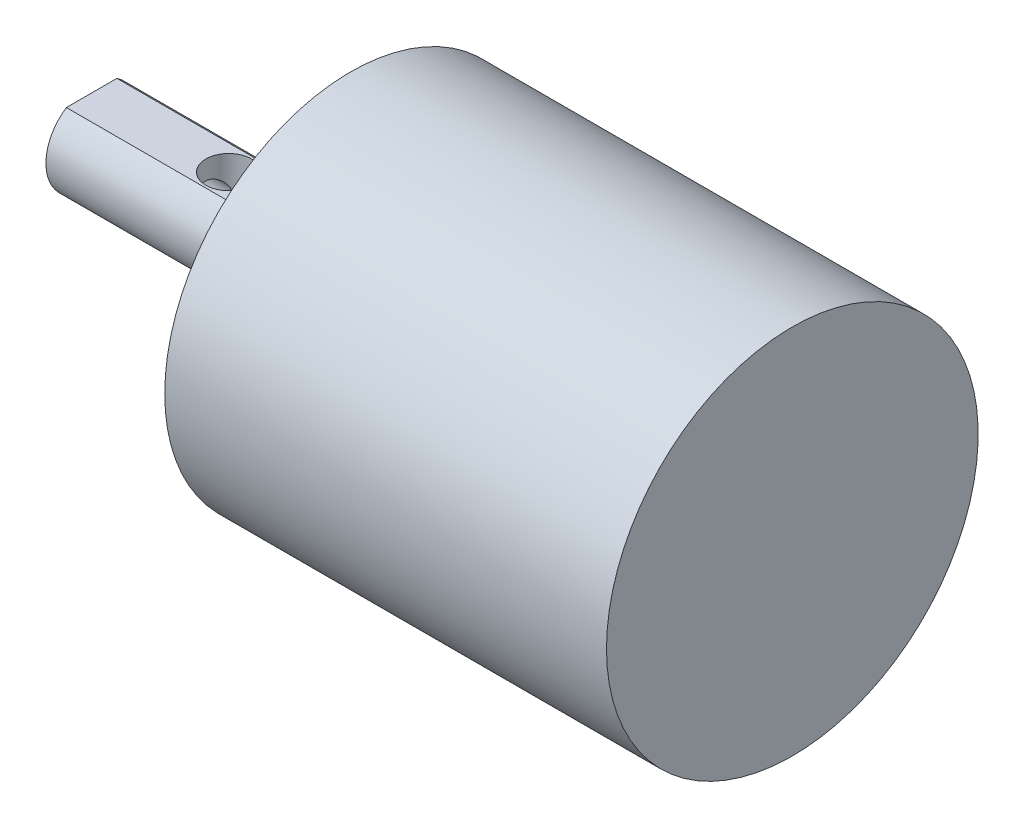
SolidWorks part; units mm, degrees
ref_plane "前视基准面" through (0, 0, 0) normal (0, 0, 1) x (1, 0, 0)
ref_plane "上视基准面" through (0, 0, 0) normal (0, 1, 0) x (1, 0, 0)
ref_plane "右视基准面" through (0, 0, 0) normal (1, 0, 0) x (0, 0, -1)
sketch "草图1" plane through (0, 0, 0) normal (0, 1, 0) x (1, 0, 0)
  line L0 (0, 0) -> (-29, 0)
  line L1 (-29, 0) -> (-29, 5.7)
  line L2 (-29, 5.7) -> (-31.6, 5.7)
  line L3 (-31.6, 5.7) -> (-31.6, 9.2)
  line L4 (-31.6, 9.2) -> (-46, 9.2)
  line L5 (-46, 9.2) -> (-46, 12.2)
  line L6 (-46, 12.2) -> (0, 12.2)
  line L7 (0, 12.2) -> (0, 0)
  dimension "D1" = 29
  dimension "D2" = 5.7
  dimension "D3" = 2.6
  dimension "D4" = 3.5
  dimension "D5" = 14.4
  dimension "D6" = 3
revolve "旋转1" add sketch "草图1" angle 360 about L6
sketch "草图2" plane through (-46, 0, 0) normal (-1, 0, 0) x (0, 0, 1)
  point P0 (-12.2, 0)
sketch "草图9" plane through (-46, 0, 0) normal (-1, 0, 0) x (0, 0, 1)
  line L0 (-12.2, 2.5) -> (-10.5417, 2.5)
  line L1 (-12.2, 2.5) -> (-13.8583, 2.5)
  line L2 (-13.8583, 2.5) -> (-12.2, 2.5)
  circle A0 centre (-12.2, 0) radius 3 construction
  arc A1 (-10.5417, 2.5) -> (-13.8583, 2.5) centre (-12.2, 0) ccw
extrude "切除-拉伸3" cut sketch "草图9" against normal blind 11.5 contours L1 A1 L0
hole_wizard "M3 螺纹孔1" positions "草图10" profile "草图11" tap size "M3" standard "GB"
sketch "草图10" plane through (-46, 0, 0) normal (-1, 0, 0) x (0, 0, 1)
  point P0 (-12.2, 0)
sketch "草图11" plane through (-46, 0, -12.2) normal (0, 1, 0) x (0, 0, 1)
  line L0 (0, 0) -> (0, 8.7511)
  line L1 (0, 8.7511) -> (1.25, 8)
  line L2 (1.25, 8) -> (1.25, 0)
  line L5 (1.25, 0) -> (0, 0)
  line L10 (0, 8.7511) -> (-1.25, 8) construction
  line L11 (0, -6.35) -> (0, 107.95) construction
  dimension "螺纹孔钻头直径" = 2.5
  dimension "螺纹孔钻头深度" = 8
  dimension "导头角度" = 118
cosmetic thread "孔螺蚊线2" parameters "D1"=5.5, "D2"=3
sketch "草图12" plane through (0, 2.5, 0) normal (0, 1, 0) x (1, 0, 0)
  line L0 (-46, 10.5417) -> (-46, 13.8583) construction
  circle A0 centre (-37, 12.2) radius 1.5
  point P0 (-37, 12.2)
  dimension "D1" = 3
  dimension "D2" = 9
extrude "切除-拉伸4" cut sketch "草图12" against normal blind 11.5 contours A0
sketch "草图13" plane through (-29, 0, 0) normal (-1, 0, 0) x (0, 0, 1)
  circle A1 centre (-12.2, 9.5) radius 1.5
  circle A2 centre (-3.9728, -4.75) radius 1.5
  circle A3 centre (-20.4272, -4.75) radius 1.5
  point P11 (-12.2, 0)
  dimension "D2" = 3
  dimension "D3" = 3
hole_wizard "M3 螺纹孔2" positions "草图14" profile "草图15" tap size "M3" standard "GB"
sketch "草图14" plane through (-29, 0, 0) normal (-1, 0, 0) x (0, 0, 1)
  point P2 (-12.2, 9.5)
  point P5 (-20.4272, -4.75)
  point P8 (-3.9728, -4.75)
sketch "草图15" plane through (-29, 9.5, -12.2) normal (0, 1, 0) x (0, 0, 1)
  line L0 (0, 0) -> (0, 4.7511)
  line L1 (0, 4.7511) -> (1.25, 4)
  line L2 (1.25, 4) -> (1.25, 0)
  line L5 (1.25, 0) -> (0, 0)
  line L10 (0, 4.7511) -> (-1.25, 4) construction
  line L11 (0, -6.35) -> (0, 107.95) construction
  dimension "螺纹孔钻头直径" = 2.5
  dimension "螺纹孔钻头深度" = 4
  dimension "导头角度" = 118
cosmetic thread "孔螺蚊线3" parameters "D1"=4, "D2"=3
cosmetic thread "孔螺蚊线4" parameters "D1"=4, "D2"=3
cosmetic thread "孔螺蚊线5" parameters "D1"=4, "D2"=3
sketch "草图16" plane through (-31.6, 0, 0) normal (-1, 0, 0) x (0, 0, 1)
  line L0 (-9.6019, -1.5) -> (-12.2, -6)
  line L1 (-18.0095, -1.5) -> (-14.6921, 1.6702)
  arc A0 (-12.2, -6) -> (-18.0095, -1.5) centre (-12.2, 0) ccw
  arc A1 (-13.8583, 2.5) -> (-10.5417, 2.5) centre (-12.2, 0) ccw construction
  arc A2 (-14.6921, 1.6702) -> (-9.6019, -1.5) centre (-12.2, 0) cw
  dimension "D1" = 12
extrude "凸台-拉伸1" add sketch "草图16" along normal blind 0.5 contours A0 L1 A2 L0
sketch "草图4" plane through (-46, 0, 0) normal (-1, 0, 0) x (0, 0, 1)
  circle A0 centre (-12.2, 0) radius 1.5
  point P0 (-12.2, 0)
  dimension "D1" = 3
sketch "草图17" plane through (0, 0, 0) normal (0, 1, 0) x (1, 0, 0)
  line L0 (-46, 12.2) -> (-37, 12.2)
  point P4 (-38.5111, 12.2)
